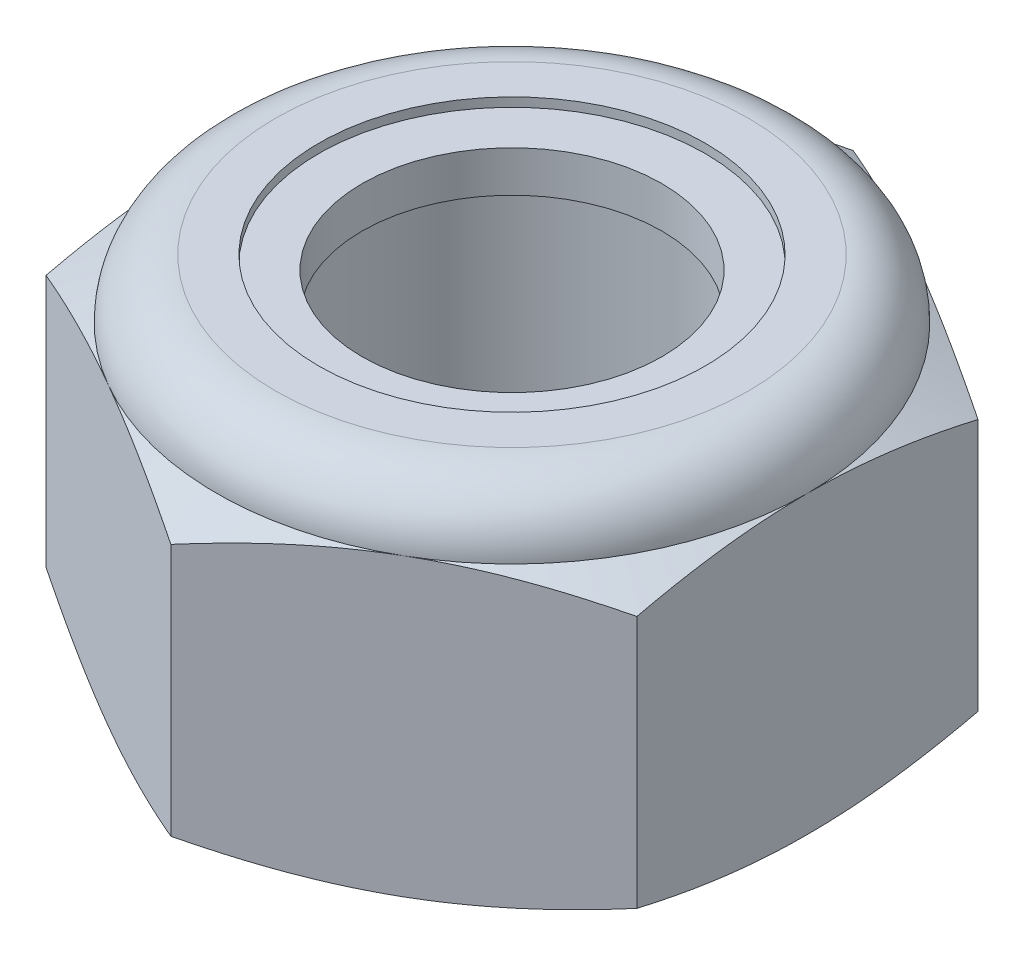
SolidWorks part; units mm, degrees
material "Alloy Steel"
ref_plane "Front" through (0, 0, 0) normal (0, 0, 1) x (1, 0, 0)
ref_plane "Top" through (0, 0, 0) normal (0, 1, 0) x (1, 0, 0)
ref_plane "Right" through (0, 0, 0) normal (1, 0, 0) x (0, 0, -1)
sketch "Sketch1" plane through (0, 0, 0) normal (0, 1, 0) x (1, 0, 0)
  line L1 (0, 5.7735) -> (-5, 2.8868)
  line L2 (-5, 2.8868) -> (-5, -2.8868)
  line L3 (-5, -2.8868) -> (0, -5.7735)
  line L4 (0, -5.7735) -> (5, -2.8868)
  line L5 (5, -2.8868) -> (5, 2.8868)
  line L6 (5, 2.8868) -> (0, 5.7735)
  circle A0 centre (0, 0) radius 5 construction
  dimension "Hex Flats" = 10
extrude "Extrude1" add sketch "Sketch1" along normal blind 6
sketch "Sketch2" plane through (0, 0, 0) normal (1, 0, 0) x (0, 0, -1)
  line L0 (-3, 0) -> (-3, 6) construction
  line L1 (0, 0) -> (3, 0)
  line L2 (0, 0) -> (0, 6)
  line L3 (0, 6) -> (3, 6)
  line L4 (3, 0) -> (3, 6)
  line L5 (-2.8868, 6) -> (2.8868, 6) construction
  line L7 (0, -3) -> (0, 0) construction
  dimension "Thread Dia" = 6
revolve "Revolve1" add sketch "Sketch2" angle 360 about L7
sketch "Sketch3" plane through (0, 0, 0) normal (1, 0, 0) x (0, 0, -1)
  line L0 (3, 6) -> (-3, 6) construction
  line L1 (-3, 6) -> (-3, 5) construction
  line L2 (-3, 5) -> (3, 6) construction
  line L3 (3, 6) -> (3.0205, 5.8767) construction
  line L4 (3.0205, 5.8767) -> (3.1644, 5.0136)
  line L5 (3.1644, 5.0136) -> (2.5791, 5.2329)
  line L6 (2.5791, 5.2329) -> (2.538, 5.4795)
  line L7 (2.538, 5.4795) -> (3.0205, 5.8767)
  line L8 (2.5586, 5.3562) -> (3.0925, 5.4452) construction
  line L9 (3, 6) -> (3, 5.4297) construction
  line L10 (3, 5.4297) -> (-3, 4.4297) construction
  line L11 (-3, 4.4297) -> (-3, 5) construction
  line L12 (-0.1784, 6) -> (0.1784, 3.8595) construction
  line L13 (-3, 0) -> (-3, 6) construction
  line L14 (0, 6) -> (3, 6) construction
  line L15 (3, 0) -> (3, 6) construction
  point P13 (0, 4.9297)
  dimension "D1" = 0.125
  dimension "D2" = 0.25
  dimension "Thread Pitch" = 1
  dimension "D4" = 60
  dimension "D5" = 1
revolve "Cut-Revolve1" [suppressed] cut sketch "Sketch3" angle 360 about L12
pattern_linear "LPattern1" [suppressed] count 6 spacing 1 along (0, 1, 0) count 2 spacing 1 along (0, 1, 0)
sketch "Sketch4" plane through (0, 0, 0) normal (1, 0, 0) x (0, 0, -1)
  line L0 (0, 6) -> (3, 6)
  line L1 (3, 6) -> (2.538, 5.7846)
  line L2 (2.538, 5.7846) -> (2.538, 0.2154)
  line L3 (2.538, 0.2154) -> (3, 0)
  line L4 (3, 0) -> (0, 0)
  line L5 (0, 0) -> (0, 6)
  line L6 (3, 0) -> (3, 6) construction
  line L7 (0, 6) -> (3, 6) construction
  line L8 (0, 0) -> (3, 0) construction
  line L9 (0, 0) -> (0, 6) construction
  line L10 (0, 6) -> (0, 6.5097) construction
  dimension "D1" = 25
revolve "Cut-Revolve2" cut sketch "Sketch4" angle 360 about L10
combine bodies "Combine1" operation type subtract main body 112 bodies to subtract 109
sketch "Sketch5" plane through (0, 0, 0) normal (1, 0, 0) x (0, 0, -1)
  line L0 (0, 0) -> (5, 0)
  line L1 (5, 0) -> (5.7735, 0.3607)
  line L2 (5.7735, 0.3607) -> (5.7735, 4.6393)
  line L3 (5.7735, 4.6393) -> (5, 5)
  line L4 (4, 6) -> (4, 7.27)
  line L5 (4, 7.27) -> (7.0435, 7.27)
  line L6 (7.0435, 7.27) -> (7.0435, -1.27)
  line L7 (7.0435, -1.27) -> (0, -1.27)
  line L8 (0, -1.27) -> (0, 0)
  line L9 (5, 5) -> (5, 0) construction
  line L10 (0, 0) -> (3, 0) construction
  line L13 (5.7735, 2.5) -> (7.0435, 2.5) construction
  line L14 (5.7735, 6) -> (5.7735, 0) construction
  line L15 (0, 0) -> (0, 7.27) construction
  line L20 (0, 7.27) -> (4, 7.27) construction
  line L22 (0, 6) -> (3, 6) construction
  arc A0 (5, 5) -> (4, 6) centre (4, 5) ccw
  dimension "D4" = 1
  dimension "D1" = 25
  dimension "D2" = 1.27
  dimension "D3" = 6
revolve "Cut-Revolve3" cut sketch "Sketch5" angle 360 about L15
sketch "Sketch6" plane through (0, 0, 0) normal (1, 0, 0) x (0, 0, -1)
  line L0 (0, 5) -> (4.8476, 5)
  line L1 (4, 5.8476) -> (3.269, 5.8476)
  line L2 (0, 7.27) -> (0, 5)
  line L3 (3.269, 7.27) -> (0, 7.27)
  line L4 (0, 7.27) -> (4, 7.27) construction
  line L5 (0, 0) -> (0, 7.27) construction
  line L6 (0, 7.27) -> (0, 44.323) construction
  line L7 (3.269, 5.8476) -> (3.269, 7.27)
  line L8 (4, 6) -> (4, 5.8476) construction
  line L9 (3.269, 5.8476) -> (2.538, 5.8476) construction
  line L10 (2.538, 5.8476) -> (2.538, 5.7846) construction
  arc A0 (4.8476, 5) -> (4, 5.8476) centre (4, 5) ccw
  arc A1 (5, 5) -> (4, 6) centre (4, 5) ccw construction
  dimension "D1" = 0.1524
revolve "Cut-Revolve4" cut sketch "Sketch6" angle 360 about L6
sketch "Sketch7" plane through (0, 0, 0) normal (1, 0, 0) x (0, 0, -1)
  line L0 (2.538, 5.0762) -> (4.7676, 5.0762)
  line L1 (4, 5.7714) -> (2.538, 5.7714)
  line L2 (2.538, 5.7714) -> (2.538, 5.0762)
  line L3 (2.538, 5.0762) -> (0, 5.0762) construction
  line L4 (0, 5.0762) -> (0, 5.7714) construction
  line L5 (0, 5.7714) -> (2.538, 5.7714) construction
  line L6 (2.538, 5.0762) -> (2.538, 5) construction
  line L7 (0, 5) -> (4.8476, 5) construction
  line L8 (4, 5.7714) -> (4, 5.8476) construction
  arc A0 (4.7676, 5.0762) -> (4, 5.7714) centre (4, 5) ccw
  arc A2 (4.8476, 5) -> (4, 5.8476) centre (4, 5) ccw construction
  dimension "D1" = 0.0762
revolve "Revolve2" add sketch "Sketch7" angle 360 about L4
equation "\"D1@Sketch3\"=\"Thread Pitch@Sketch3\"/8"
equation "\"D2@Sketch3\"=\"Thread Pitch@Sketch3\"/4"
equation "\"D5@Sketch3\"=\"Thread Pitch@Sketch3\""
equation "\"D4@LPattern1\"=\"Thread Pitch@Sketch3\""
equation "\"D3@LPattern1\"=\"Thread Pitch@Sketch3\""
equation "\"D1@LPattern1\"=\"Height@Extrude1\"/\"Thread Pitch@Sketch3\""
equation "\"D4@Sketch5\"=\"Height@Extrude1\"/6"
